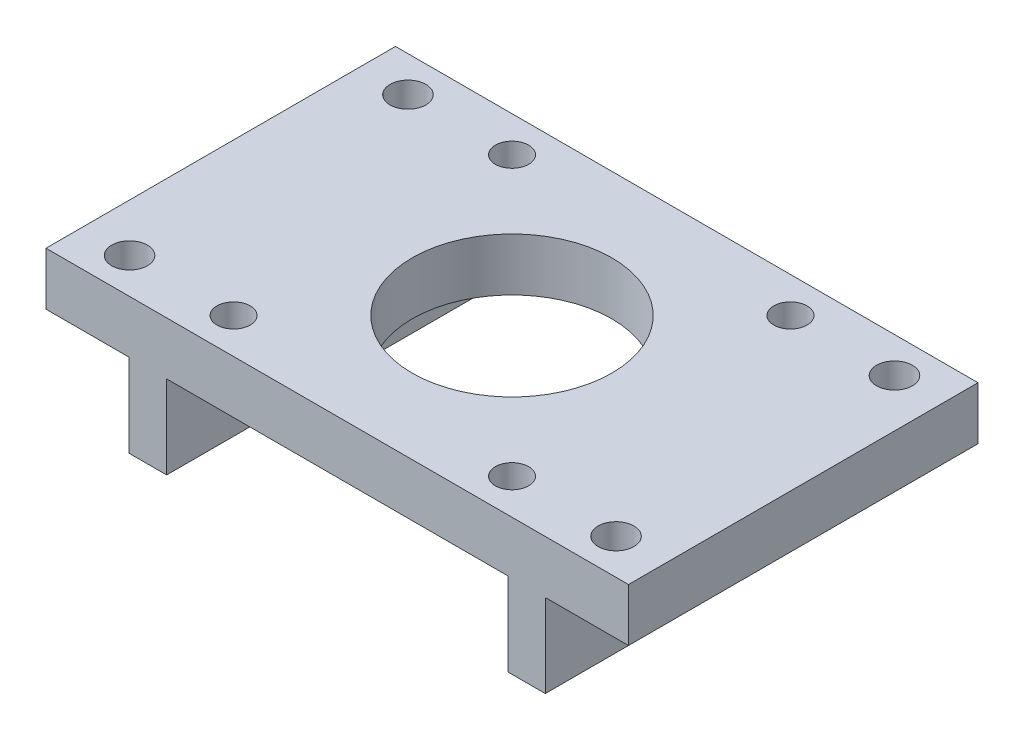
SolidWorks part; units mm, degrees
ref_plane "Front Plane" through (0, 0, 0) normal (0, 0, 1) x (1, 0, 0)
ref_plane "Top Plane" through (0, 0, 0) normal (0, 1, 0) x (1, 0, 0)
ref_plane "Right Plane" through (0, 0, 0) normal (1, 0, 0) x (0, 0, -1)
sketch "Sketch1" plane through (0, 0, 0) normal (0, 1, 0) x (1, 0, 0)
  line L1 (35, -21) -> (-35, -21)
  line L2 (35, -21) -> (35, 21)
  line L3 (35, 21) -> (-35, 21)
  line L4 (-35, -21) -> (-35, 21)
  line L5 (35, -21) -> (-35, 21) construction
  line L6 (35, 21) -> (-35, -21) construction
  point P0 (0, 0)
  dimension "D1" = 70
  dimension "D2" = 42
extrude "Boss-Extrude1" add sketch "Sketch1" along normal mid plane 6.35
sketch "Sketch3" plane through (0, -3.175, 0) normal (0, -1, 0) x (1, 0, 0)
  line L0 (-35, 21) -> (35, 21) construction
  line L1 (25, -21) -> (-25, -21)
  line L2 (25, -21) -> (25, 21)
  line L3 (25, 21) -> (-25, 21)
  line L4 (-25, -21) -> (-25, 21)
  line L5 (25, -21) -> (-25, 21) construction
  line L6 (25, 21) -> (-25, -21) construction
  line L7 (-20.5, 21) -> (-20.5, -21)
  line L8 (20.5, -21) -> (20.5, 21)
  line L9 (-20.5, 0) -> (20.5, 0) construction
  point P0 (0, 0)
  point P14 (0, 0)
  line M7 (-35, -21) -> (35, -21)
  line M9 (35, 21) -> (-35, 21)
  dimension "D1" = 50
  dimension "D2" = 41
extrude "Boss-Extrude2" add sketch "Sketch3" along normal blind 10 contours L7 L3 L4 M7 | L8 L2 M7 M9
sketch "Sketch4" plane through (0, 3.175, 0) normal (0, 1, 0) x (1, 0, 0)
  circle A0 centre (0, 0) radius 12
  dimension "D1" = 24
hole_wizard "Ø1.0mm Dowel Hole1" positions "Sketch5" profile "Sketch6" hole size "Ø1.0" standard "ANSI Metric" end condition up to next
sketch "Sketch5" plane through (0, 3.175, 0) normal (0, 1, 0) x (1, 0, 0)
  line L0 (-16.73, 16.73) -> (16.73, 16.73) construction
  line L1 (16.73, 16.73) -> (16.73, -16.73) construction
  line L2 (16.73, -16.73) -> (-16.73, -16.73) construction
  line L3 (-16.73, -16.73) -> (-16.73, 16.73) construction
  point P0 (-16.73, 16.73)
  point P2 (16.73, 16.73)
  point P4 (16.73, -16.73)
  point P6 (-16.73, -16.73)
  point P15 (0, 16.73)
  point P19 (16.73, 0)
  dimension "D1" = 33.46
sketch "Sketch6" plane through (-16.73, 3.175, -16.73) normal (1, 0, 0) x (0, 0, 1)
  line L0 (0, 0) -> (0, 6.35)
  line L1 (0, 6.35) -> (2, 6.35)
  line L2 (2, 6.35) -> (2, 0)
  line L5 (2, 0) -> (0, 0)
  line L11 (0, -6.35) -> (0, 107.95) construction
  dimension "Thru Hole Dia." = 4
  dimension "Thru Hole Depth" = 6.35
hole_wizard "Ø1.0mm Dowel Hole2" positions "Sketch7" profile "Sketch8" hole size "Ø1.0" standard "ANSI Metric" end condition up to next
sketch "Sketch7" plane through (0, 3.175, 0) normal (0, 1, 0) x (1, 0, 0)
  line L0 (-29.23, 16.73) -> (-16.73, 16.73) construction
  line L2 (-29.23, -16.73) -> (-16.73, -16.73) construction
  point P0 (-29.23, 16.73)
  point P2 (-29.23, -16.73)
  point P13 (-29.23, 16.8462)
  dimension "D2" = 12.5
sketch "Sketch8" plane through (-29.23, 3.175, -16.73) normal (1, 0, 0) x (0, 0, 1)
  line L0 (0, 0) -> (0, 6.35)
  line L1 (0, 6.35) -> (2.15, 6.35)
  line L2 (2.15, 6.35) -> (2.15, 0)
  line L5 (2.15, 0) -> (0, 0)
  line L11 (0, -6.35) -> (0, 107.95) construction
  dimension "Thru Hole Dia." = 4.3
  dimension "Thru Hole Depth" = 6.35
mirror "Mirror1" about plane through (0, 0, 0) normal (1, 0, 0) of "Ø1.0mm Dowel Hole2"
extrude "Cut-Extrude1" cut sketch "Sketch4" against normal through all
